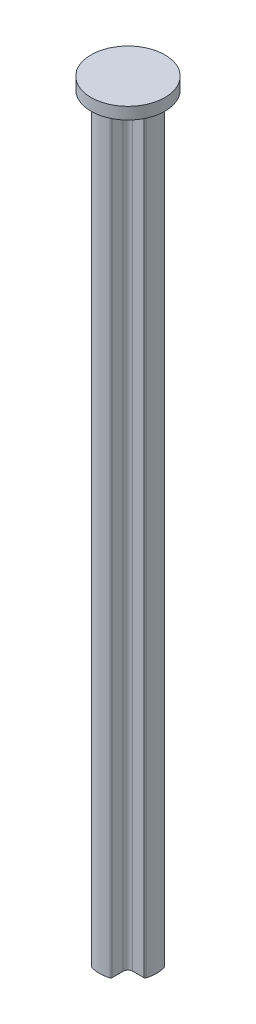
SolidWorks part; units mm, degrees
ref_plane "Front Plane" through (0, 0, 0) normal (0, 0, 1) x (1, 0, 0)
ref_plane "Top Plane" through (0, 0, 0) normal (0, 1, 0) x (1, 0, 0)
ref_plane "Right Plane" through (0, 0, 0) normal (1, 0, 0) x (0, 0, -1)
sketch "Sketch1" plane through (0, 0, 0) normal (0, 1, 0) x (1, 0, 0)
  circle A0 centre (0, 0) radius 3.1
  dimension "D1" = 6.2
extrude "Boss-Extrude1" add sketch "Sketch1" along normal blind 64
sketch "Sketch2" plane through (0, 0, 0) normal (0, 1, 0) x (1, 0, 0)
  line L0 (1.24, -0.84) -> (2.1777, -0.84)
  line L2 (-0.84, 2.1777) -> (-0.84, 1.24)
  line L4 (0.84, 2.1777) -> (0.84, 1.24)
  line L5 (-0.84, 2.2482) -> (0.84, -2.2482) construction
  line L6 (-0.84, -2.2482) -> (0.84, 2.2482) construction
  line L7 (-2.1777, 0.84) -> (-1.24, 0.84)
  line L9 (-2.1777, -0.84) -> (-1.24, -0.84)
  line L11 (-2.2482, 0.84) -> (2.2482, -0.84) construction
  line L12 (-2.2482, -0.84) -> (2.2482, 0.84) construction
  line L13 (-0.84, -1.24) -> (-0.84, -2.1777)
  line L14 (1.24, 0.84) -> (2.1777, 0.84)
  line L15 (0.84, -1.24) -> (0.84, -2.1777)
  arc A0 (0.7722, 2.2724) -> (-0.7722, 2.2724) centre (0, 0) ccw
  arc A1 (-2.2724, 0.7722) -> (-2.2724, -0.7722) centre (0, 0) ccw
  arc A2 (-0.7722, -2.2724) -> (0.7722, -2.2724) centre (0, 0) ccw
  arc A3 (2.2724, -0.7722) -> (2.2724, 0.7722) centre (0, 0) ccw
  arc A4 (-0.84, -2.1777) -> (-0.7722, -2.2724) centre (-0.74, -2.1777) ccw
  arc A5 (0.7722, -2.2724) -> (0.84, -2.1777) centre (0.74, -2.1777) ccw
  arc A6 (2.2724, -0.7722) -> (2.1777, -0.84) centre (2.1777, -0.74) cw
  arc A7 (2.1777, 0.84) -> (2.2724, 0.7722) centre (2.1777, 0.74) cw
  arc A8 (-2.1777, 0.84) -> (-2.2724, 0.7722) centre (-2.1777, 0.74) ccw
  arc A9 (-2.2724, -0.7722) -> (-2.1777, -0.84) centre (-2.1777, -0.74) ccw
  arc A10 (-0.7722, 2.2724) -> (-0.84, 2.1777) centre (-0.74, 2.1777) ccw
  arc A11 (0.7722, 2.2724) -> (0.84, 2.1777) centre (0.74, 2.1777) cw
  arc A12 (-1.24, -0.84) -> (-0.84, -1.24) centre (-1.24, -1.24) cw
  arc A13 (1.24, -0.84) -> (0.84, -1.24) centre (1.24, -1.24) ccw
  arc A14 (1.24, 0.84) -> (0.84, 1.24) centre (1.24, 1.24) cw
  arc A15 (-0.84, 1.24) -> (-1.24, 0.84) centre (-1.24, 1.24) cw
  circle A16 centre (0, 0) radius 3.1
  point P40 (-0.84, -0.84)
  point P43 (0.84, -0.84)
  dimension "D1" = 4.8
  dimension "D4" = 0.1
  dimension "D5" = 0.4
  dimension "D6" = 6.2
  dimension "D2" = 1.68
  dimension "D3" = 1.68
extrude "Cut-Extrude1" cut sketch "Sketch2" along normal blind 63
